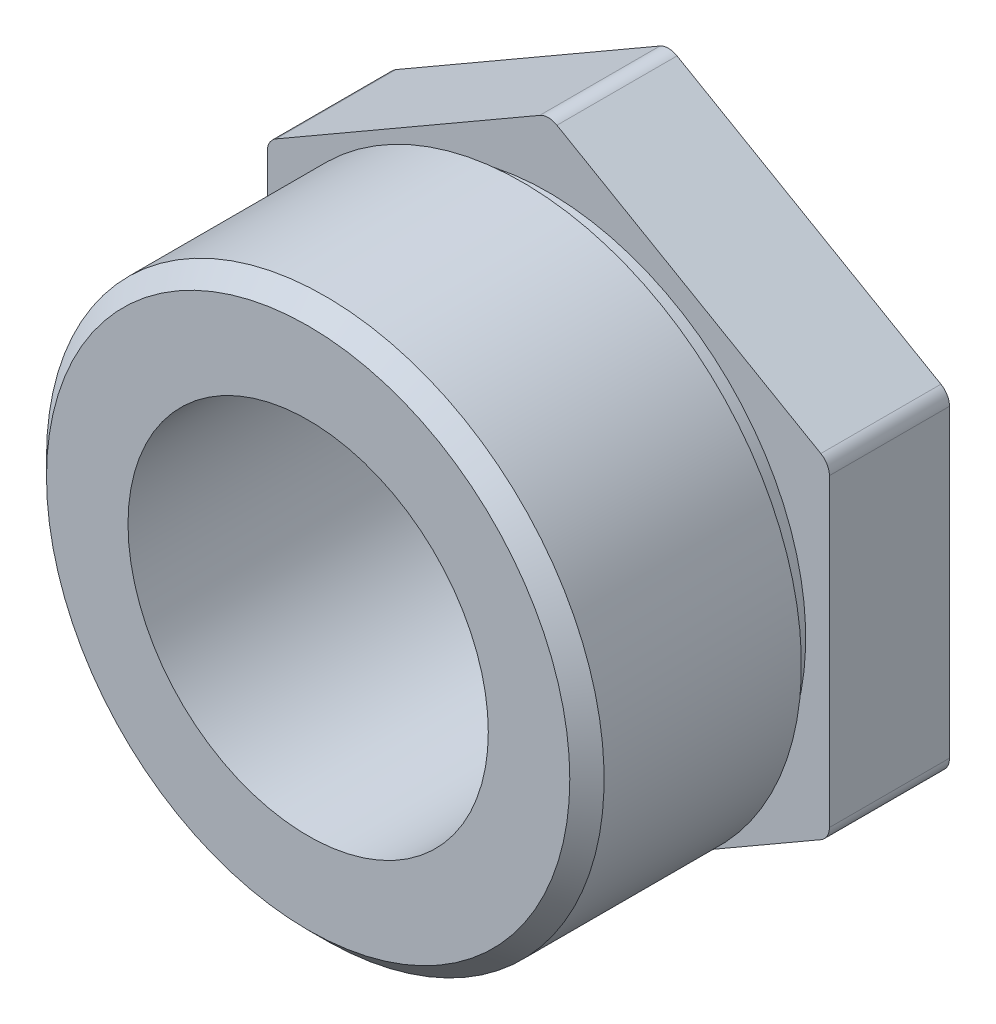
SolidWorks part; units mm, degrees
ref_plane "Front Plane" through (0, 0, 0) normal (0, 0, 1) x (1, 0, 0)
ref_plane "Top Plane" through (0, 0, 0) normal (0, 1, 0) x (1, 0, 0)
ref_plane "Right Plane" through (0, 0, 0) normal (1, 0, 0) x (0, 0, -1)
sketch "Sketch1" plane through (0, 0, 0) normal (0, 0, 1) x (1, 0, 0)
  circle A0 centre (0, 0) radius 32.5
  dimension "D1" = 65
extrude "Boss-Extrude1" add sketch "Sketch1" along normal blind 42
cosmetic thread "Cosmetic Thread1" parameters "D1"=25, "D2"=59.61
sketch "Sketch2" plane through (0, 0, 42) normal (0, 0, 1) x (1, 0, 0)
  circle A0 centre (0, 0) radius 30
  circle A1 centre (0, 0) radius 32.5 construction
  circle A2 centre (0, 0) radius 32.5
  dimension "D1" = 60
extrude "Cut-Extrude1" cut sketch "Sketch2" along normal blind 3 from offset 28 offset against normal yes
sketch "Sketch3" plane through (0, 0, 0) normal (0, 0, -1) x (-1, 0, 0)
  line L1 (0, -37.8288) -> (32.7607, -18.9144)
  line L2 (32.7607, -18.9144) -> (32.7607, 18.9144)
  line L3 (32.7607, 18.9144) -> (0, 37.8288)
  line L4 (0, 37.8288) -> (-32.7607, 18.9144)
  line L5 (-32.7607, 18.9144) -> (-32.7607, -18.9144)
  line L6 (-32.7607, -18.9144) -> (0, -37.8288)
  circle A0 centre (0, 0) radius 32.7607 construction
extrude "Boss-Extrude2" add sketch "Sketch3" against normal blind 14
fillet "Fillet1" radius 2 6 edges at (0, -37.8288, 7) (-32.7607, -18.9144, 7) (-32.7607, 18.9144, 7) (32.7607, -18.9144, 7) (32.7607, 18.9144, 7) (0, 37.8288, 7)
chamfer "Chamfer1" distance 2 angle 45 1 edges at (32.5, 0, 42)
sketch "Sketch4" plane through (0, 0, 42) normal (0, 0, 1) x (1, 0, 0)
  circle A0 centre (0, 0) radius 21
  dimension "D1" = 42
extrude "Cut-Extrude3" cut sketch "Sketch4" against normal through all
